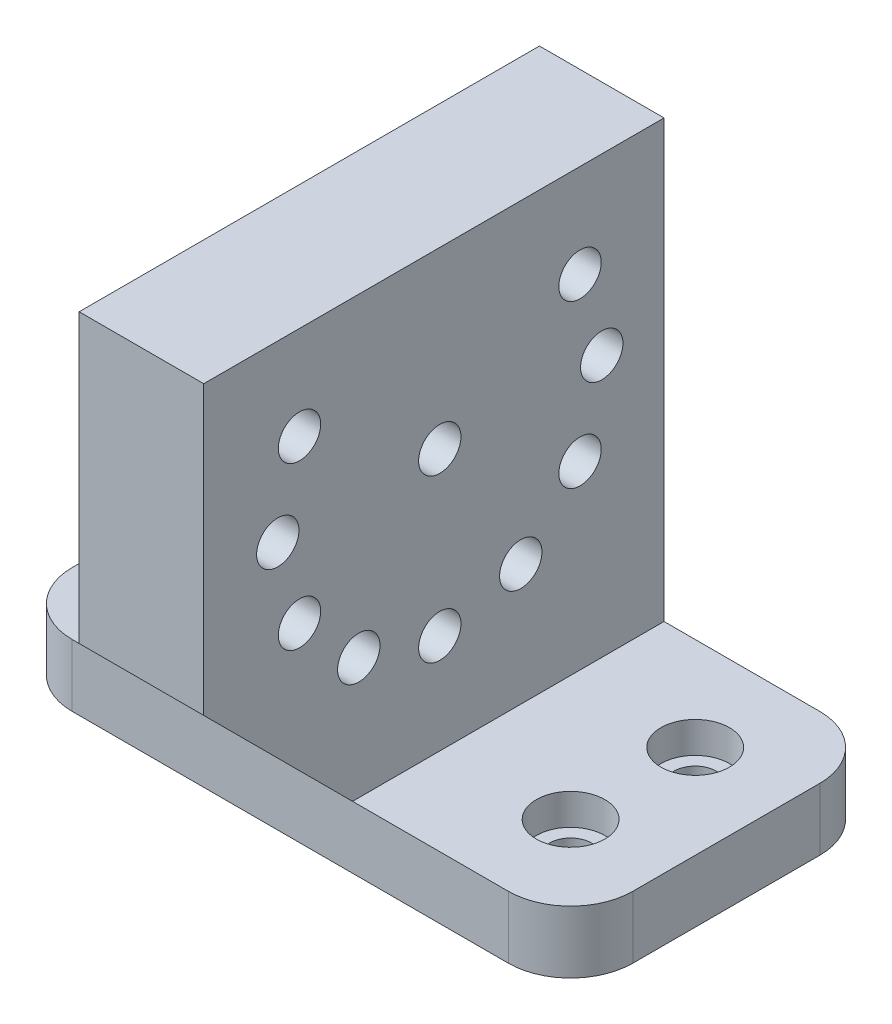
SolidWorks part; units mm, degrees
ref_plane "Front Plane" through (0, 0, 0) normal (0, 0, 1) x (1, 0, 0)
ref_plane "Top Plane" through (0, 0, 0) normal (0, 1, 0) x (1, 0, 0)
ref_plane "Right Plane" through (0, 0, 0) normal (1, 0, 0) x (0, 0, -1)
sketch "Sketch3" plane through (0, 0, 0) normal (0, 1, 0) x (1, 0, 0)
  line L0 (-22.5, 0) -> (22.5, 0) construction
  line L1 (-17.5, -12.5) -> (17.5, -12.5)
  line L2 (-22.5, -7.5) -> (-22.5, 7.5)
  line L3 (-17.5, 12.5) -> (17.5, 12.5)
  line L4 (22.5, -7.5) -> (22.5, 7.5)
  line L5 (-22.5, -12.5) -> (22.5, 12.5) construction
  line L6 (-22.5, 12.5) -> (22.5, -12.5) construction
  line L7 (0, 12.5) -> (0, -12.5) construction
  circle A0 centre (-15, 5) radius 1.7
  circle A1 centre (15, 5) radius 1.7
  circle A2 centre (15, -5) radius 1.7
  circle A3 centre (-15, -5) radius 1.7
  arc A4 (17.5, -12.5) -> (22.5, -7.5) centre (17.5, -7.5) ccw
  arc A5 (17.5, 12.5) -> (22.5, 7.5) centre (17.5, 7.5) cw
  arc A6 (-22.5, 7.5) -> (-17.5, 12.5) centre (-17.5, 7.5) cw
  arc A7 (-17.5, -12.5) -> (-22.5, -7.5) centre (-17.5, -7.5) cw
  point P0 (0, 0)
  dimension "D3" = 3.4
  dimension "D6" = 5
  dimension "D1" = 45
  dimension "D2" = 25
  dimension "D4" = 15
  dimension "D5" = 5
extrude "Boss-Extrude2" add sketch "Sketch3" along normal blind 5
sketch "Sketch8" plane through (0, 0, 0) normal (1, 0, 0) x (0, 0, -1)
  line L0 (12.5, 5) -> (12.5, 40)
  line L1 (-7.5, 5) -> (7.5, 5) construction
  line L3 (12.5, 5) -> (-12.5, 5)
  line L4 (-7.5, 5) -> (-12.5, 5) construction
  line L6 (-12.5, 5) -> (-9.4429, 0)
  line L7 (-12.5, 5) -> (-24.4429, 16.9429)
  line L8 (-5.5, 26) -> (-5.5, 13) construction
  line L9 (-9.4429, 0) -> (-24.4429, 0)
  line L10 (-24.4429, 0) -> (-24.4429, 40)
  line L11 (-24.4429, 40) -> (12.5, 40)
  line L12 (-5.5, 26) -> (1, 14.7417) construction
  circle A0 centre (-5.5, 26) radius 1.7
  circle A1 centre (-5.5, 13) radius 1.7
  circle A2 centre (-12, 14.7417) radius 1.7
  circle A3 centre (-16.7583, 19.5) radius 1.7
  circle A4 centre (-18.5, 26) radius 1.7
  circle A5 centre (-16.7583, 32.5) radius 1.7
  circle A6 centre (-12, 37.2583) radius 1.7 [skipped]
  circle A7 centre (-5.5, 39) radius 1.7 [skipped]
  circle A8 centre (1, 37.2583) radius 1.7 [skipped]
  circle A9 centre (5.7583, 32.5) radius 1.7
  circle A10 centre (7.5, 26) radius 1.7
  circle A11 centre (5.7583, 19.5) radius 1.7
  circle A12 centre (1, 14.7417) radius 1.7
  point P41 (-5.5, 26)
  dimension "D5" = 3.4
  dimension "D7" = 13
  dimension "D1" = 90
  dimension "D2" = 15
  dimension "D3" = 25
  dimension "D4" = 35
  dimension "D6" = 14
  dimension "D8" = 135
  dimension "D9" = 18
  dimension "D10" = 0
  dimension "D11" = 30
  dimension "D12" = 8
extrude "Boss-Extrude4" add sketch "Sketch8" along normal mid plane 10 contours L11 L10 L7 L3 L0 A12 A11 A10 A9 A5 A4 A3 A2 A1 A0
sketch "Sketch10" plane through (0, 5, 0) normal (0, 1, 0) x (1, 0, 0)
  circle A0 centre (15, -5) radius 2.75
  circle A1 centre (-15, -5) radius 2.75
  circle A2 centre (-15, 5) radius 2.75
  circle A3 centre (15, 5) radius 2.75
  dimension "D1" = 2
  dimension "D2" = 2
extrude "Cut-Extrude1" cut sketch "Sketch10" against normal blind 2.5
